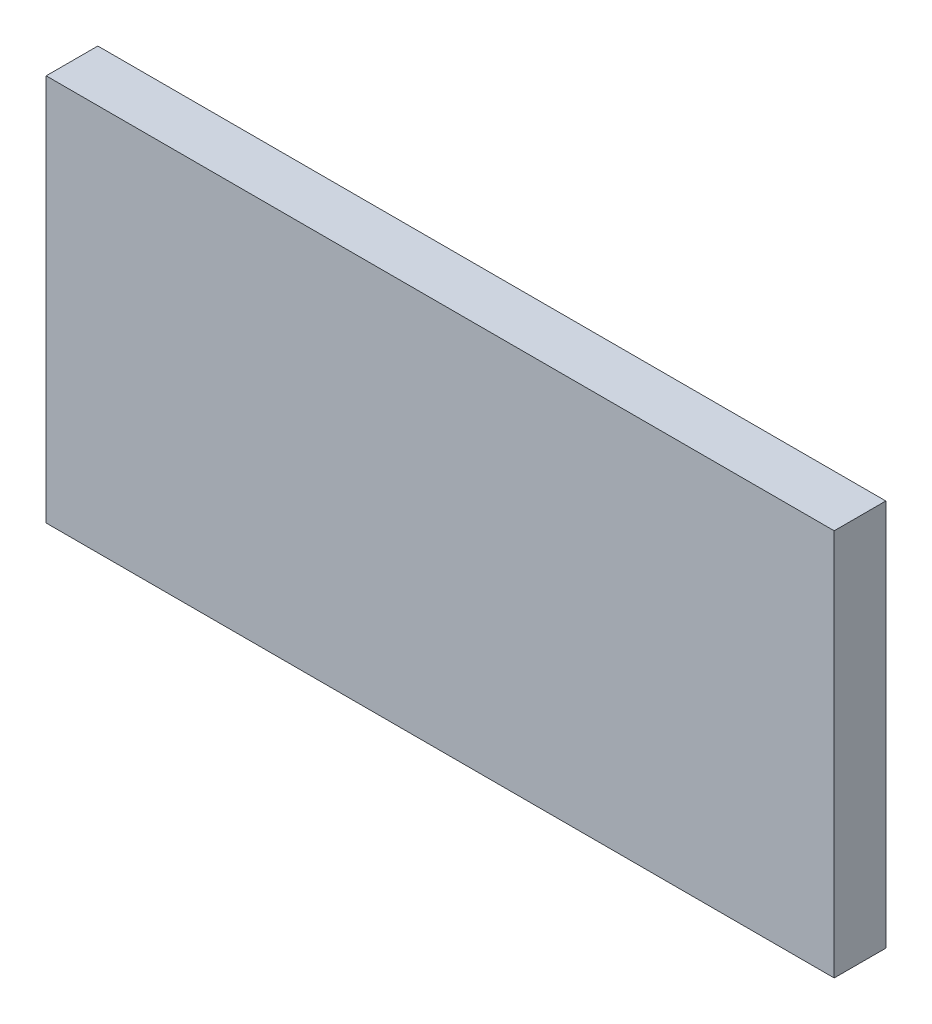
SolidWorks part; units mm, degrees
ref_plane "Plano frontal" through (0, 0, 0) normal (0, 0, 1) x (1, 0, 0)
ref_plane "Plano superior" through (0, 0, 0) normal (0, 1, 0) x (1, 0, 0)
ref_plane "Plano direito" through (0, 0, 0) normal (1, 0, 0) x (0, 0, -1)
sketch "Esboço1" plane through (0, 0, 0) normal (0, 0, 1) x (1, 0, 0)
  line L0 (-56.203, 0) -> (-56.203, 50) construction
  line L1 (-30.5194, -15) -> (30.5194, -15)
  line L2 (-30.5194, -15) -> (-30.5194, 15)
  line L3 (-30.5194, 15) -> (30.5194, 15)
  line L4 (30.5194, -15) -> (30.5194, 15)
  line L5 (-30.5194, -15) -> (30.5194, 15) construction
  line L6 (-30.5194, 15) -> (30.5194, -15) construction
  line L7 (-56.203, 50) -> (-106.203, 14.9896) construction
  line L8 (-106.203, 14.9896) -> (-106.203, 0) construction
  line L9 (-106.203, 0) -> (-56.203, 0) construction
  point P0 (0, 0)
  point P8 (-106.203, 12.782)
  point P11 (0, 0)
  dimension "D1" = 50
  dimension "D2" = 50
  dimension "D3" = 35
  dimension "D4" = 30
extrude "Ressalto-extrusão1" add sketch "Esboço1" along normal blind 4
